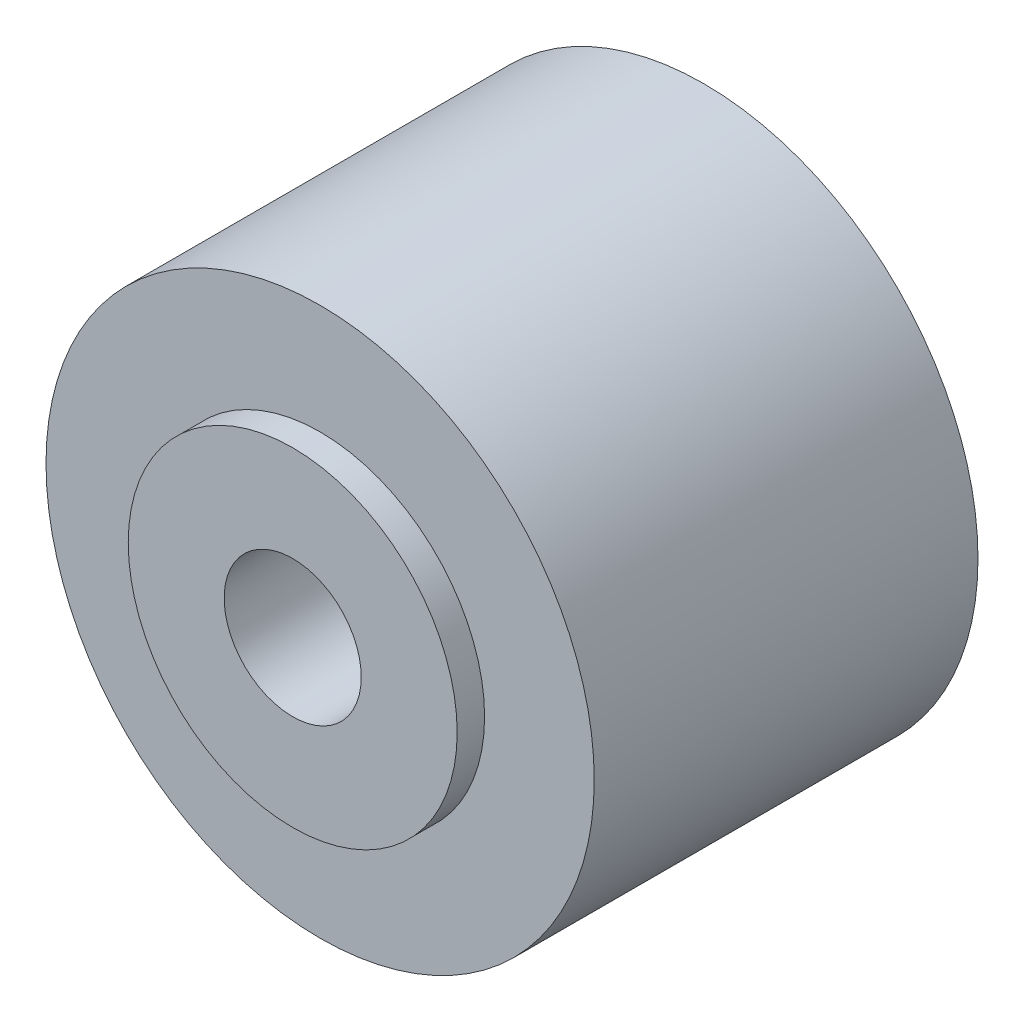
SolidWorks part; units mm, degrees
ref_plane "Front" through (0, 0, 0) normal (0, 0, 1) x (1, 0, 0)
ref_plane "Top" through (0, 0, 0) normal (0, 1, 0) x (1, 0, 0)
ref_plane "Right" through (0, 0, 0) normal (1, 0, 0) x (0, 0, -1)
sketch "Sketch1" plane through (0, 0, 0) normal (0, 0, 1) x (1, 0, 0)
  circle A0 centre (0, 0) radius 1.25
  circle A1 centre (0, 0) radius 3
  dimension "D1" = 6
  dimension "D2" = 2.5
extrude "Boss-Extrude1" add sketch "Sketch1" along normal mid plane 8
sketch "Sketch2" plane through (0, 0, 0) normal (0, 0, 1) x (1, 0, 0)
  circle A0 centre (0, 0) radius 5
  circle A1 centre (0, 0) radius 3
  circle A2 centre (0, 0) radius 3 construction
  dimension "D1" = 10
extrude "Boss-Extrude2" add sketch "Sketch2" along normal mid plane 7
